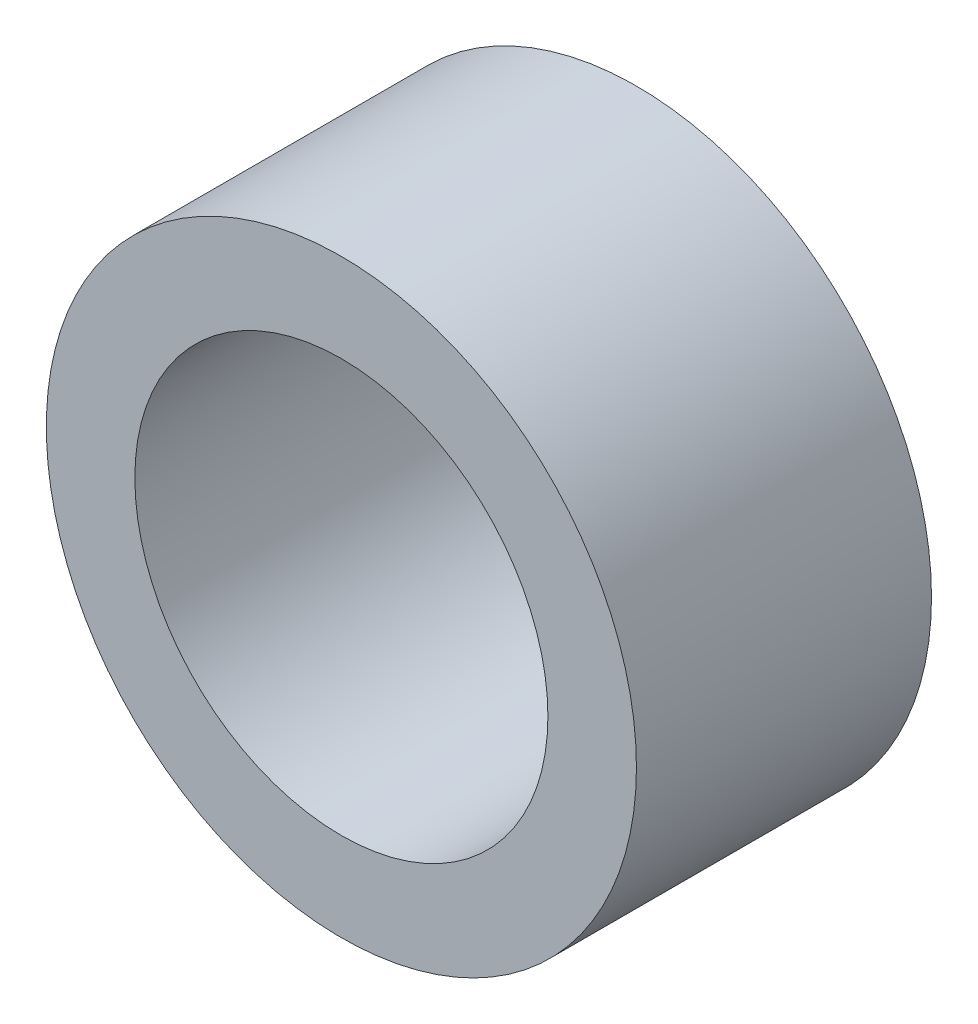
SolidWorks part; units mm, degrees
ref_plane "Front Plane" through (0, 0, 0) normal (0, 0, 1) x (1, 0, 0)
ref_plane "Top Plane" through (0, 0, 0) normal (0, 1, 0) x (1, 0, 0)
ref_plane "Right Plane" through (0, 0, 0) normal (1, 0, 0) x (0, 0, -1)
sketch "Sketch1" plane through (0, 0, 0) normal (0, 0, 1) x (1, 0, 0)
  circle A0 centre (0, 0) radius 1.5
  circle A1 centre (0, 0) radius 1.05
extrude "Spacer" add sketch "Sketch1" along normal blind 1.5
